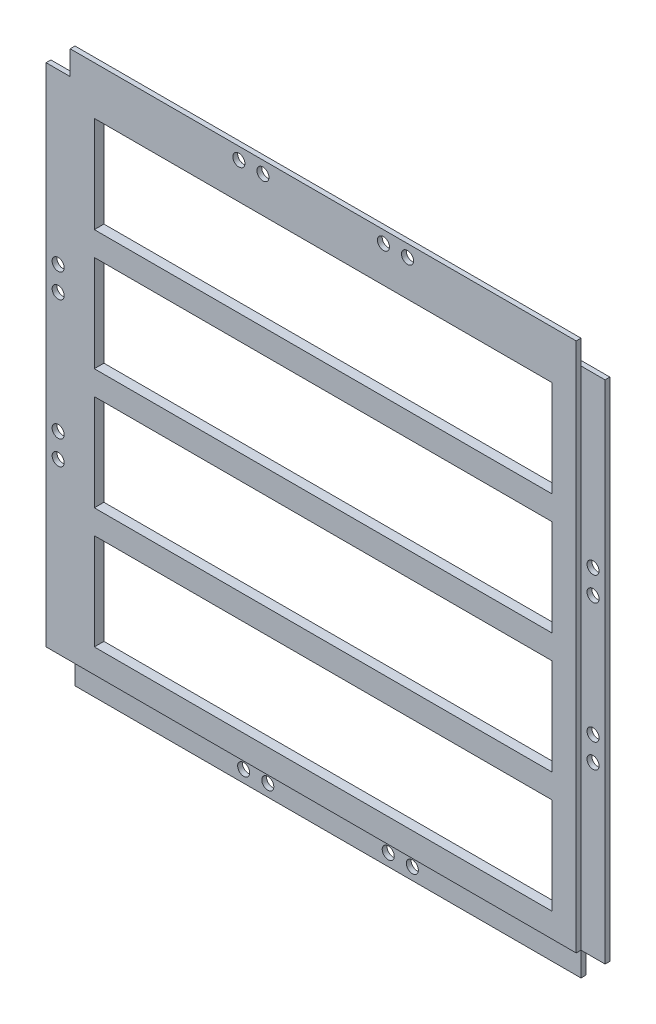
SolidWorks part; units mm, degrees
ref_plane "前视基准面" through (0, 0, 0) normal (0, 0, 1) x (1, 0, 0)
ref_plane "上视基准面" through (0, 0, 0) normal (0, 1, 0) x (1, 0, 0)
ref_plane "右视基准面" through (0, 0, 0) normal (1, 0, 0) x (0, 0, -1)
other "Configuration Table"
sketch "草图1" plane through (0, 0, 0) normal (0, 0, 1) x (1, 0, 0)
  line L1 (10, 0) -> (220, 0)
  line L2 (0, 10) -> (0, 220)
  line L3 (10, 230) -> (220, 230)
  line L4 (230, 10) -> (230, 220)
  line L7 (0, 220) -> (10, 220)
  line L8 (10, 230) -> (10, 220)
  line L11 (230, 220) -> (220, 220)
  line L12 (220, 230) -> (220, 220)
  line L15 (230, 10) -> (220, 10)
  line L16 (220, 0) -> (220, 10)
  line L19 (0, 10) -> (10, 10)
  line L20 (10, 0) -> (10, 10)
  dimension "D1" = 230
  dimension "D2" = 230
  dimension "D3" = 10
  dimension "D4" = 10
  dimension "D5" = 10
  dimension "D6" = 10
  dimension "D7" = 10
  dimension "D8" = 10
  dimension "D9" = 10
  dimension "D10" = 10
extrude "凸台-拉伸1" add sketch "草图1" along normal blind 4 contours L20 L1 L16 L15 L4 L11 L12 L3 L8 L7 L2 L19
sketch "草图2" plane through (0, 0, 4) normal (0, 0, 1) x (1, 0, 0)
  line L5 (10, 10) -> (220, 10)
  line L10 (10, 10) -> (10, 0)
  line L19 (10, 0) -> (220, 0)
  line L20 (220, 10) -> (220, 0)
  line L21 (220, 10) -> (230, 10)
  line L22 (220, 10) -> (220, 220)
  line L23 (220, 220) -> (230, 220)
  line L24 (230, 10) -> (230, 220)
extrude "切除-拉伸1" cut sketch "草图2" against normal blind 2
sketch "草图3" plane through (0, 0, 0) normal (0, 0, -1) x (-1, 0, 0)
  line L5 (-220, 230) -> (-10, 230)
  line L18 (-220, 230) -> (-220, 220)
  line L19 (-220, 220) -> (-10, 220)
  line L20 (-10, 230) -> (-10, 220)
  line L21 (-10, 220) -> (0, 220)
  line L22 (-10, 220) -> (-10, 10)
  line L23 (-10, 10) -> (0, 10)
  line L24 (0, 220) -> (0, 10)
  line M30 (-10, 10) -> (0, 10)
  line M31 (0, 10) -> (0, 220)
  line M32 (0, 220) -> (-10, 220)
  line M33 (-10, 220) -> (-10, 230)
  line M34 (-10, 230) -> (-220, 230)
  line M35 (-220, 230) -> (-220, 220)
extrude "切除-拉伸2" cut sketch "草图3" against normal blind 2 contours L19 M35 M33 M34 | L22 M32 M30 M31
sketch "草图4" plane through (0, 0, 4) normal (0, 0, 1) x (1, 0, 0)
  line L0 (-20.4287, 115) -> (279.4097, 115) construction
  line L1 (115, 272.1934) -> (115, -21.9098) construction
  line L2 (10, 0) -> (220, 0) construction
  line L3 (0, 10) -> (0, 220) construction
  circle A0 centre (5, 80) radius 2.5
  circle A2 centre (5, 90) radius 2.5
  circle A3 centre (5, 150) radius 2.5
  circle A4 centre (5, 140) radius 2.5
  circle A5 centre (225, 80) radius 2.5
  circle A6 centre (225, 90) radius 2.5
  circle A7 centre (225, 140) radius 2.5
  circle A8 centre (225, 150) radius 2.5
  circle A9 centre (80, 5) radius 2.5
  circle A10 centre (90, 5) radius 2.5
  circle A11 centre (140, 5) radius 2.5
  circle A12 centre (150, 5) radius 2.5
  circle A13 centre (150, 225) radius 2.5
  circle A14 centre (140, 225) radius 2.5
  circle A15 centre (90, 225) radius 2.5
  circle A16 centre (80, 225) radius 2.5
  dimension "D4" = 5
  dimension "D1" = 115
  dimension "D2" = 115
  dimension "D3" = 80
  dimension "D5" = 5
  dimension "D6" = 10
  dimension "D7" = 80
  dimension "D8" = 5
  dimension "D9" = 10
extrude "切除-拉伸3" cut sketch "草图4" against normal through all
sketch "草图5" plane through (0, 0, 4) normal (0, 0, 1) x (1, 0, 0)
  line L1 (20, 20) -> (210, 20)
  line L2 (20, 20) -> (20, 60)
  line L3 (20, 60) -> (210, 60)
  line L4 (210, 20) -> (210, 60)
  line L6 (10, 0) -> (220, 0) construction
  line L7 (220, 230) -> (220, 10) construction
  line L8 (10, 10) -> (10, 0) construction
  line L19 (20, 70) -> (20, 110)
  line L20 (20, 70) -> (210, 70)
  line L21 (210, 70) -> (210, 110)
  line L22 (20, 110) -> (210, 110)
  line L23 (20, 120) -> (20, 160)
  line L24 (20, 120) -> (210, 120)
  line L25 (210, 120) -> (210, 160)
  line L26 (20, 160) -> (210, 160)
  line L27 (20, 170) -> (20, 210)
  line L28 (20, 170) -> (210, 170)
  line L29 (210, 170) -> (210, 210)
  line L30 (20, 210) -> (210, 210)
  point P11 (10, 5)
  dimension "D1" = 20
  dimension "D2" = 10
  dimension "D3" = 40
  dimension "D4" = 10
  dimension "D5" = 4
extrude "切除-拉伸4" cut sketch "草图5" against normal through all
